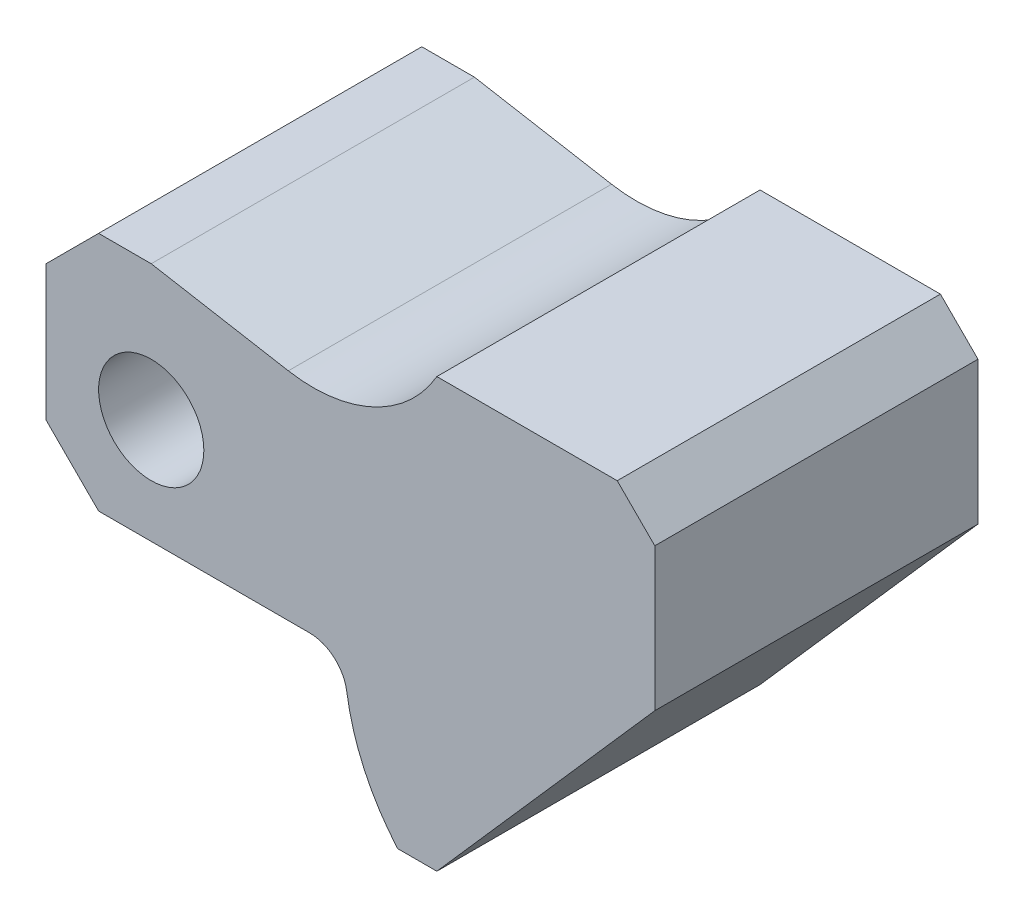
SolidWorks part; units mm, degrees
material "AISI 1020"
ref_plane "Front Plane" through (0, 0, 0) normal (0, 0, 1) x (1, 0, 0)
ref_plane "Top Plane" through (0, 0, 0) normal (0, 1, 0) x (1, 0, 0)
ref_plane "Right Plane" through (0, 0, 0) normal (1, 0, 0) x (0, 0, -1)
sketch "Sketch1" plane through (0, 0, 0) normal (0, 0, 1) x (1, 0, 0)
  line L0 (0, 7) -> (0, 25)
  line L1 (7, 32) -> (14, 32)
  line L2 (14, 32) -> (32.2431, 28.7833)
  line L3 (52, 38) -> (76, 38)
  line L4 (81, 33) -> (81, 14)
  line L5 (81, 14) -> (52, -19)
  line L6 (52, -19) -> (46.7881, -19)
  line L7 (35.0666, 0) -> (7, 0)
  line L8 (0, 25) -> (7, 32)
  line L9 (7, 0) -> (0, 7)
  line L10 (76, 38) -> (81, 33)
  arc A0 (32.2431, 28.7833) -> (52, 38) centre (35.5424, 47.4946) ccw
  arc A1 (35.0666, 0) -> (40.0123, -4.2647) centre (35.0666, -5) cw
  arc A2 (40.0123, -4.2647) -> (46.7881, -19) centre (68.697, 0) ccw
  circle A3 centre (14, 14) radius 7
  point P0 (0, 0)
  point P1 (0, 32)
  point P9 (81, 38)
  dimension "D8" = 19
  dimension "D15" = 5
  dimension "D16" = 29
  dimension "D19" = 14
  dimension "D1" = 81
  dimension "D2" = 57
  dimension "D3" = 32
  dimension "D4" = 14
  dimension "D5" = 10
  dimension "D9" = 29
  dimension "D10" = 24
  dimension "D11" = 29
  dimension "D12" = 19
  dimension "D14" = 19
  dimension "D17" = 14
  dimension "D18" = 14
extrude "Boss-Extrude1" add sketch "Sketch1" along normal blind 43
equation "\"A\"= 81"
equation "\"B\"= 57"
equation "\"C\"= 43"
equation "\"D1@Sketch1\"=\"A\""
equation "\"D2@Sketch1\"=\"B\""
equation "\"D1@Boss-Extrude1\"=\"C\""
